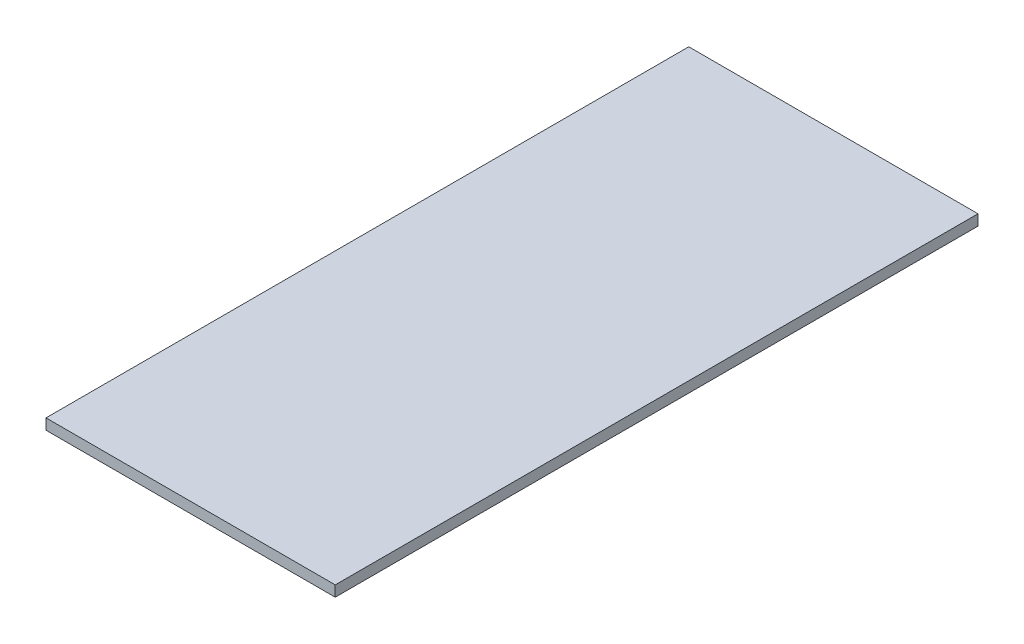
SolidWorks part; units mm, degrees
material "ASTM A36 Steel"
ref_plane "Front Plane" through (0, 0, 0) normal (0, 0, 1) x (1, 0, 0)
ref_plane "Top Plane" through (0, 0, 0) normal (0, 1, 0) x (1, 0, 0)
ref_plane "Right Plane" through (0, 0, 0) normal (1, 0, 0) x (0, 0, -1)
sketch "Sketch1" plane through (0, 0, 0) normal (0, 1, 0) x (1, 0, 0)
  line L1 (42.8625, 95.25) -> (-42.8625, 95.25)
  line L2 (42.8625, 95.25) -> (42.8625, -95.25)
  line L3 (42.8625, -95.25) -> (-42.8625, -95.25)
  line L4 (-42.8625, 95.25) -> (-42.8625, -95.25)
  line L5 (42.8625, 95.25) -> (-42.8625, -95.25) construction
  line L6 (42.8625, -95.25) -> (-42.8625, 95.25) construction
  point P0 (0, 0)
  point P6 (0, 0)
  dimension "D1" = 85.725
  dimension "D2" = 190.5
extrude "Boss-Extrude1" add sketch "Sketch1" along normal blind 3.175
shell "Shell1" thickness 1.27
fillet "Fillet1" radius 3.175 4 edges at (-41.5925, 0.9525, -93.98) (41.5925, 0.9525, -93.98) (41.5925, 0.9525, 93.98) (-41.5925, 0.9525, 93.98)
